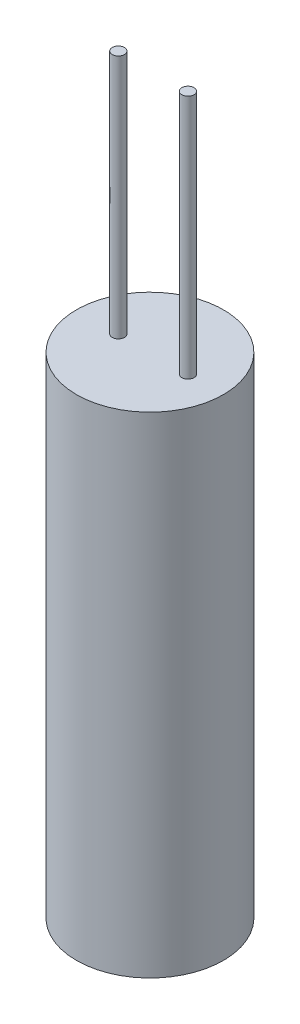
SolidWorks part; units mm, degrees
material "Медь"
ref_plane "Спереди" through (0, 0, 0) normal (0, 0, 1) x (1, 0, 0)
ref_plane "Сверху" through (0, 0, 0) normal (0, 1, 0) x (1, 0, 0)
ref_plane "Справа" through (0, 0, 0) normal (1, 0, 0) x (0, 0, -1)
other "Configuration Table"
sketch "Эскиз1" plane through (0, 0, 0) normal (0, 1, 0) x (1, 0, 0)
  circle A0 centre (0, 0) radius 3
  dimension "D1" = 6
extrude "Бобышка-Вытянуть1" add sketch "Эскиз1" along normal blind 20
sketch "Эскиз2" plane through (0, 20, 0) normal (0, 1, 0) x (1, 0, 0)
  circle A0 centre (-1.2897, 0) radius 0.25
  circle A1 centre (1.5503, 0) radius 0.25
  dimension "D1" = 0.5
  dimension "D2" = 2.84
extrude "Бобышка-Вытянуть2" add sketch "Эскиз2" along normal blind 10
